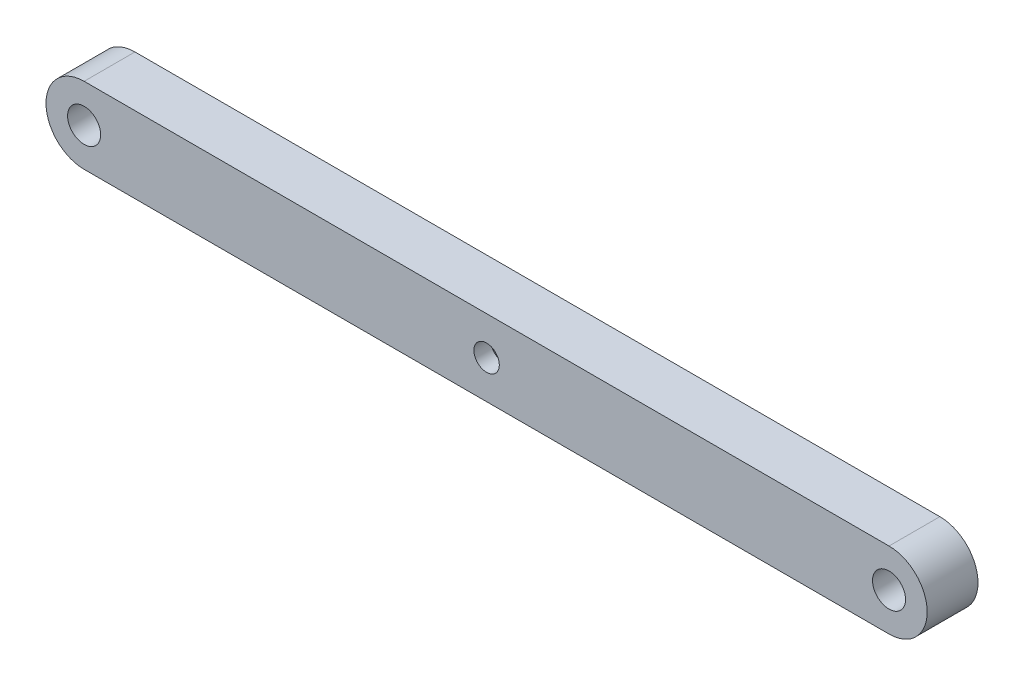
SolidWorks part; units mm, degrees
ref_plane "Front Plane" through (0, 0, 0) normal (0, 0, 1) x (1, 0, 0)
ref_plane "Top Plane" through (0, 0, 0) normal (0, 1, 0) x (1, 0, 0)
ref_plane "Right Plane" through (0, 0, 0) normal (1, 0, 0) x (0, 0, -1)
ref_plane "Plane1" through (0, 0, 6) normal (0, 0, 1) x (1, 0, 0)
sketch "Sketch1" plane through (0, 0, 6) normal (0, 0, 1) x (1, 0, 0)
  line L0 (47.5, 4.5) -> (-47.5, 4.5)
  line L1 (-47.5, -4.5) -> (47.5, -4.5)
  arc A0 (-47.5, 4.5) -> (-47.5, -4.5) centre (-47.5, 0) ccw
  arc A1 (47.5, -4.5) -> (47.5, 4.5) centre (47.5, 0) ccw
extrude "Boss-Extrude1" add sketch "Sketch1" against normal blind 6
hole_wizard "Ø3.9 (3.9) Diameter Hole1" positions "Sketch3" profile "Sketch2" hole size "Ø3.9" standard "ANSI Metric"
sketch "Sketch3" plane through (0, 0, 0) normal (0, 0, -1) x (-1, 0, 0)
  point P0 (47.5, 0)
  point P1 (-47.5, 0)
sketch "Sketch2" plane through (-47.5, 0, 0) normal (1, 0, 0) x (0, 1, 0)
  line L0 (0, 0) -> (0, 6)
  line L1 (0, 6) -> (1.95, 6)
  line L2 (1.95, 6) -> (1.95, 0)
  line L5 (1.95, 0) -> (0, 0)
  line L11 (0, -6.35) -> (0, 107.95) construction
  dimension "Thru Hole Dia." = 3.9
  dimension "Thru Hole Depth" = 6
hole_wizard "CSK for M2.5 Flat Head Machine Screw1" positions "Sketch5" profile "Sketch4" countersink size "M2.5" standard "ANSI Metric"
sketch "Sketch5" plane through (0, 0, 0) normal (0, 0, -1) x (-1, 0, 0)
  point P0 (0, 0)
sketch "Sketch4" plane through (0, 0, 0) normal (1, 0, 0) x (0, 1, 0)
  line L0 (0, 0) -> (0, 6)
  line L1 (0, 6) -> (1.5, 6)
  line L2 (1.5, 6) -> (1.5, 4)
  line L3 (1.5, 4) -> (2.5, 3)
  line L4 (2.5, 3) -> (2.5, 0)
  line L6 (2.5, 0) -> (0, 0)
  line L7 (-1.5, 4) -> (-2.5, 3) construction
  line L11 (0, -6.35) -> (0, 107.95) construction
  dimension "Thru Hole Dia." = 3
  dimension "Thru Hole Depth" = 6
  dimension "C'Sink Dia." = 5
  dimension "C'Sink Angle" = 90
  dimension "Head Clearance" = 3
